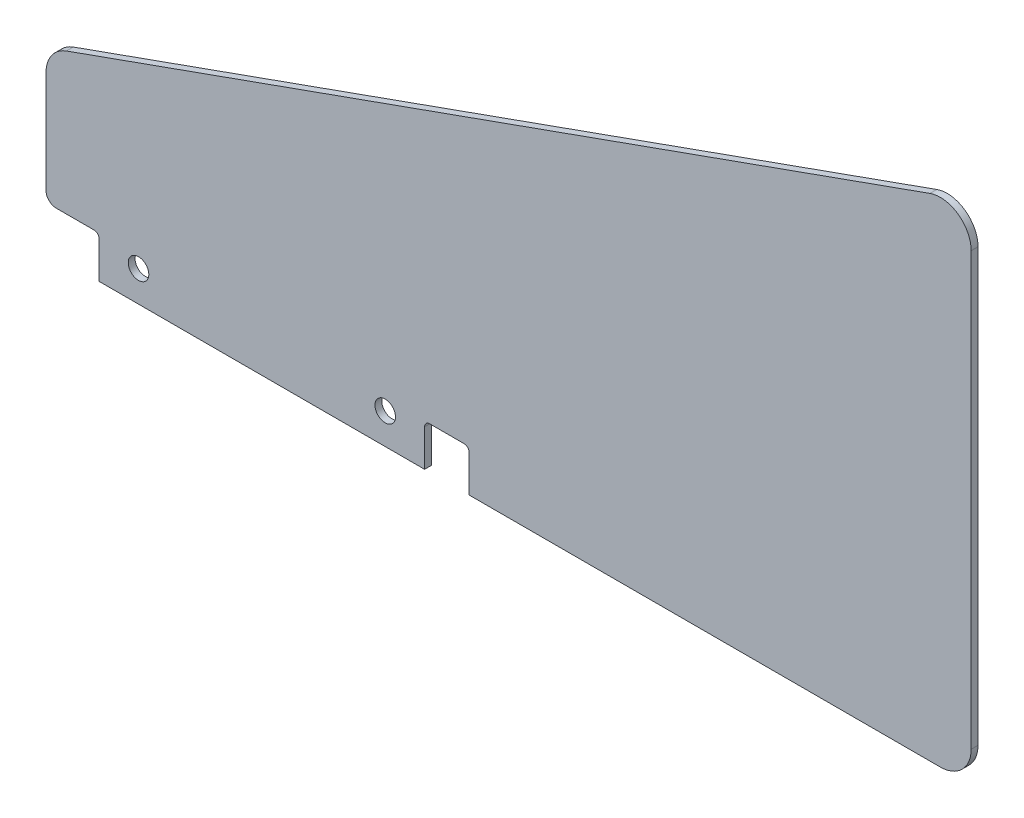
SolidWorks part; units mm, degrees
ref_plane "Alzado" through (0, 0, 0) normal (0, 0, 1) x (1, 0, 0)
ref_plane "Planta" through (0, 0, 0) normal (0, 1, 0) x (1, 0, 0)
ref_plane "Vista lateral" through (0, 0, 0) normal (1, 0, 0) x (0, 0, -1)
sketch "Model" plane through (0, 0, 0) normal (0, 0, 1) x (1, 0, 0)
  line L0 (147.3999, 168.7619) -> (216.1499, 168.7619)
  line L1 (85.6499, 176.3869) -> (85.6499, 191.2619)
  line L2 (220.6499, 236.2619) -> (220.6499, 173.2619)
  line L3 (88.6364, 195.4997) -> (214.6364, 240.4997)
  line L4 (87.1499, 174.8869) -> (92.6499, 174.8869)
  line L5 (93.3999, 174.1369) -> (93.3999, 168.7619)
  line L6 (141.6499, 174.8869) -> (146.6499, 174.8869)
  line L7 (147.3999, 174.1369) -> (147.3999, 168.7619)
  line L8 (140.8999, 168.7619) -> (140.8999, 174.1369)
  line L9 (93.3999, 168.7619) -> (140.8999, 168.7619)
  circle A0 centre (99.1499, 173.2619) radius 1.5
  circle A1 centre (135.1499, 173.2619) radius 1.5
  arc A2 (220.6499, 236.2619) -> (214.6364, 240.4997) centre (216.1499, 236.2619) ccw
  arc A3 (88.6364, 195.4997) -> (85.6499, 191.2619) centre (90.1499, 191.2619) ccw
  arc A4 (216.1499, 168.7619) -> (220.6499, 173.2619) centre (216.1499, 173.2619) ccw
  arc A5 (93.3999, 174.1369) -> (92.6499, 174.8869) centre (92.6499, 174.1369) ccw
  arc A6 (147.3999, 174.1369) -> (146.6499, 174.8869) centre (146.6499, 174.1369) ccw
  arc A7 (141.6499, 174.8869) -> (140.8999, 174.1369) centre (141.6499, 174.1369) ccw
  arc A8 (85.6499, 176.3869) -> (87.1499, 174.8869) centre (87.1499, 176.3869) ccw
extrude "Saliente-Extruir1" add sketch "Model" along normal blind 1
